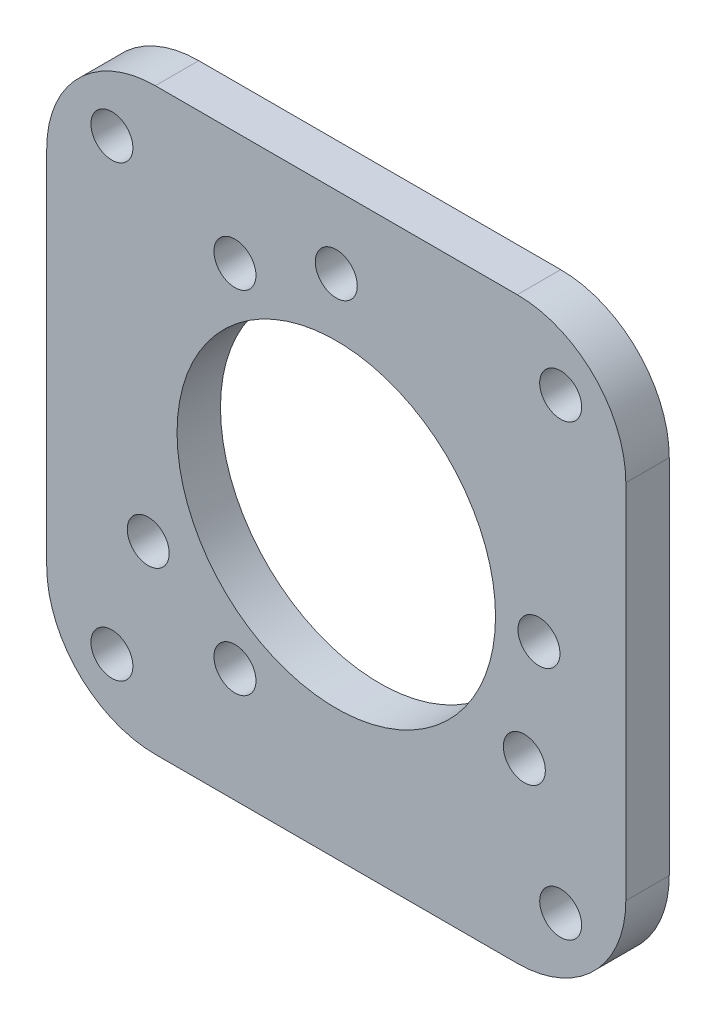
SolidWorks part; units mm, degrees
ref_plane "前视基准面" through (0, 0, 0) normal (0, 0, 1) x (1, 0, 0)
ref_plane "上视基准面" through (0, 0, 0) normal (0, 1, 0) x (1, 0, 0)
ref_plane "右视基准面" through (0, 0, 0) normal (1, 0, 0) x (0, 0, -1)
sketch "草图1" plane through (0, 0, 0) normal (0, 0, 1) x (1, 0, 0)
  line L1 (-12.5, 20) -> (12.5, 20)
  line L2 (-20, 12.5) -> (-20, -12.5)
  line L3 (-12.5, -20) -> (12.5, -20)
  line L4 (20, 12.5) -> (20, -12.5)
  line L5 (-24.736, 24.736) -> (25.264, -25.264) construction
  line L6 (-25.0035, -25.0035) -> (24.9965, 24.9965) construction
  arc A0 (-12.5, 20) -> (-20, 12.5) centre (-12.5, 12.5) ccw
  arc A1 (20, 12.5) -> (12.5, 20) centre (12.5, 12.5) ccw
  arc A2 (12.5, -20) -> (20, -12.5) centre (12.5, -12.5) ccw
  arc A3 (-20, -12.5) -> (-12.5, -20) centre (-12.5, -12.5) ccw
  point P6 (-20, 0)
  dimension "D3" = 7.5
  dimension "D4" = 7.5
  dimension "D5" = 7.5
  dimension "D6" = 7.5
  dimension "D7" = 20
  dimension "D1" = 40
  dimension "D2" = 40
  dimension "D8" = 20
sketch "草图2" plane through (0, 0, 0) normal (0, 0, 1) x (1, 0, 0)
  line L0 (-41.9557, 0) -> (43.5443, 0) construction
  line L1 (0, 41.0858) -> (0, -45.4368) construction
  line L2 (-25.0035, -25.0035) -> (24.9965, 24.9965) construction
  line L3 (-10.9689, 18.9987) -> (0, 0) construction
  line L4 (0, 0) -> (18.7578, -10.8298) construction
  line L5 (0, 0) -> (-11.9837, -20.7563) construction
  line L6 (0, 0) -> (-17.7159, -10.2283) construction
  circle A0 centre (15.5, 15.5) radius 1.45
  circle A1 centre (-15.5, 15.5) radius 1.45
  circle A2 centre (15.5, -15.5) radius 1.45
  circle A3 centre (-15.5, -15.5) radius 1.45
  circle A4 centre (0, 15) radius 1.45
  circle A5 centre (14, 0) radius 1.45
  circle A6 centre (-7, -12.1244) radius 1.45
  circle A7 centre (-12.9904, -7.5) radius 1.45
  circle A8 centre (12.9904, -7.5) radius 1.45
  circle A9 centre (-7, 12.1244) radius 1.45
  circle A10 centre (0, 0) radius 11
  dimension "D1" = 15.5
  dimension "D2" = 2.9
  dimension "D3" = 15
  dimension "D4" = 2.9
  dimension "D7" = 2.9
  dimension "D9" = 2.9
  dimension "D12" = 2.9
  dimension "D15" = 2.9
  dimension "D16" = 30
  dimension "D17" = 2.9
  dimension "D19" = 22
  dimension "D5" = 30
  dimension "D6" = 14
  dimension "D8" = 14
  dimension "D10" = 30
  dimension "D11" = 15
  dimension "D13" = 30
  dimension "D14" = 14
  dimension "D18" = 15
extrude "凸台-拉伸1" add sketch "草图1" along normal blind 3
extrude "切除-拉伸1" cut sketch "草图2" along normal blind 5
